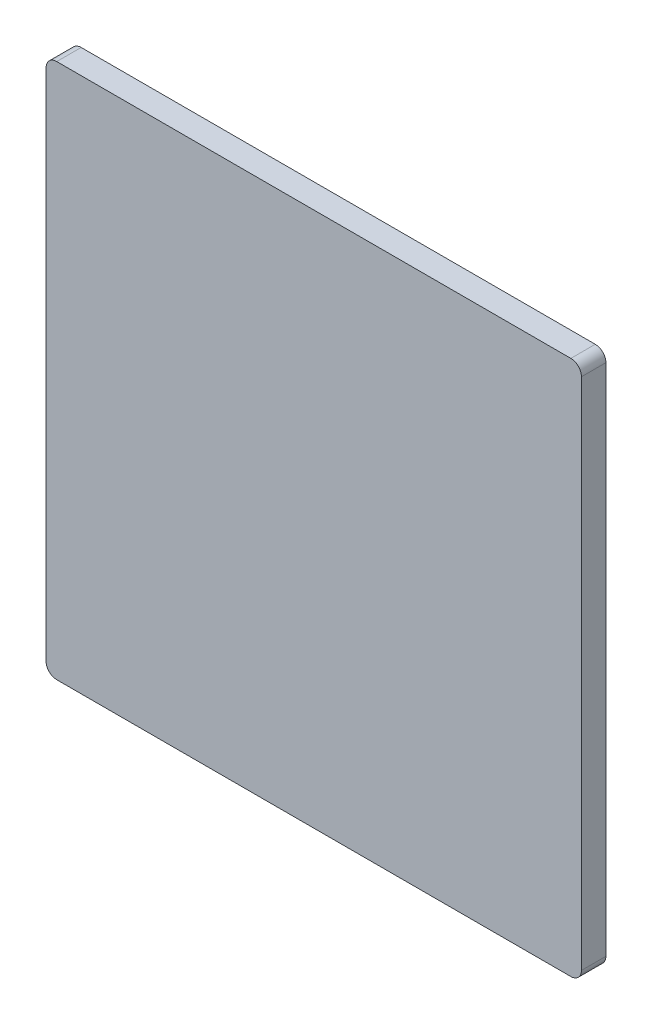
SolidWorks part; units mm, degrees
ref_plane "Спереди" through (0, 0, 0) normal (0, 0, 1) x (1, 0, 0)
ref_plane "Сверху" through (0, 0, 0) normal (0, 1, 0) x (1, 0, 0)
ref_plane "Справа" through (0, 0, 0) normal (1, 0, 0) x (0, 0, -1)
sketch "Эскиз1" plane through (0, 0, 0) normal (0, 0, 1) x (1, 0, 0)
  line L1 (-12.6, -12.6) -> (12.6, -12.6)
  line L2 (-12.6, -12.6) -> (-12.6, 12.6)
  line L3 (-12.6, 12.6) -> (12.6, 12.6)
  line L4 (12.6, -12.6) -> (12.6, 12.6)
  line L5 (-12.6, -12.6) -> (12.6, 12.6) construction
  line L6 (-12.6, 12.6) -> (12.6, -12.6) construction
  point P0 (0, 0)
  dimension "D1" = 25.2
extrude "Бобышка-Вытянуть1" add sketch "Эскиз1" along normal blind 1.15
fillet "Скругление1" radius 0.5 4 edges at (12.6, -12.6, 0.575) (-12.6, -12.6, 0.575) (-12.6, 12.6, 0.575) (12.6, 12.6, 0.575)
